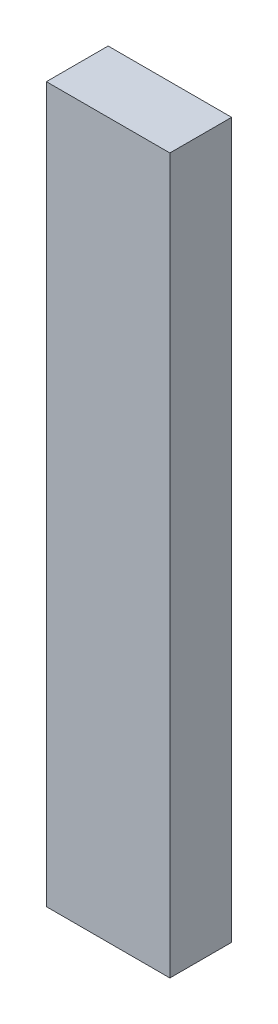
SolidWorks part; units mm, degrees
ref_plane "Front Plane" through (0, 0, 0) normal (0, 0, 1) x (1, 0, 0)
ref_plane "Top Plane" through (0, 0, 0) normal (0, 1, 0) x (1, 0, 0)
ref_plane "Right Plane" through (0, 0, 0) normal (1, 0, 0) x (0, 0, -1)
sketch "Sketch1" plane through (0, 0, 0) normal (0, 1, 0) x (1, 0, 0)
  line L1 (0, 0) -> (44.45, 0)
  line L2 (0, 0) -> (0, 22.225)
  line L3 (0, 22.225) -> (44.45, 22.225)
  line L4 (44.45, 0) -> (44.45, 22.225)
  dimension "D1" = 44.45
  dimension "D2" = 22.225
extrude "Boss-Extrude1" add sketch "Sketch1" along normal blind 257.175
